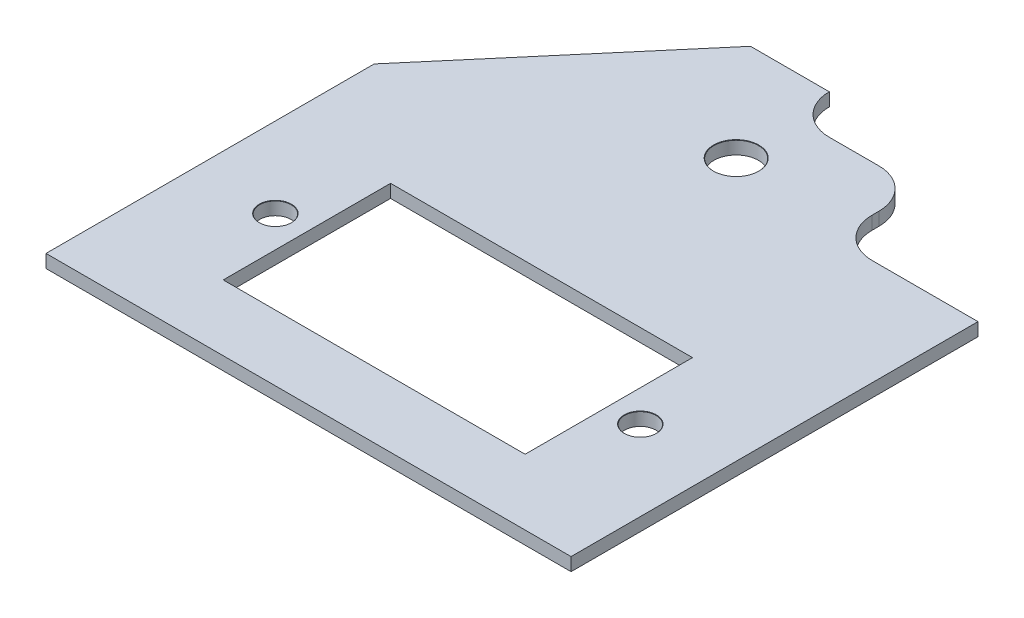
SolidWorks part; units mm, degrees
ref_plane "Front Plane" through (0, 0, 0) normal (0, 0, 1) x (1, 0, 0)
ref_plane "Top Plane" through (0, 0, 0) normal (0, 1, 0) x (1, 0, 0)
ref_plane "Right Plane" through (0, 0, 0) normal (1, 0, 0) x (0, 0, -1)
sketch "Sketch1" plane through (0, 0, 0) normal (0, 1, 0) x (1, 0, 0)
  line L0 (-3, 0) -> (-9, 0)
  line L5 (0, -3) -> (3.77, -3)
  line L6 (6.77, -6) -> (6.77, -6.5)
  line L7 (9.77, -6.5) -> (6.77, -6.5) construction
  line L8 (9.77, -9.5) -> (9.77, -15.5)
  line L9 (-9, 0) -> (-9, -15.5)
  line L10 (-9, -15.5) -> (9.77, -15.5)
  arc A0 (-3, 0) -> (0, -3) centre (0, 0) ccw
  arc A1 (6.77, -6) -> (3.77, -3) centre (3.77, -6) ccw
  arc A2 (6.77, -6.5) -> (9.77, -9.5) centre (9.77, -6.5) ccw
  dimension "D1" = 6
  dimension "D2" = 6
  dimension "D3" = 0.5
  dimension "D4" = 3.77
extrude "Boss-Extrude1" add sketch "Sketch1" along normal blind 1 contours L9 L10 L8 A2 L6 A1 L5 A0 L0
hole_wizard "M3 Clearance Hole1" positions "Sketch2" profile "Sketch3" hole size "M3" standard "ANSI Metric" end condition through all
sketch "Sketch2" plane through (0, 1, 0) normal (0, 1, 0) x (1, 0, 0)
  line L1 (-2.1713, -7.9213) -> (-2.1213, -7.9213) construction
  line L2 (-2.1213, -7.9213) -> (-2.1213, -2.1213) construction
  arc A1 (-3, 0) -> (0, -3) centre (0, 0) ccw construction
  point P0 (-2.1713, -7.9213)
  dimension "D1" = 5.8
  dimension "D2" = 0.05
sketch "Sketch3" plane through (-2.1713, 1, 7.9213) normal (1, 0, 0) x (0, 0, 1)
  line L0 (0, 0) -> (0, 1)
  line L1 (0, 1) -> (1.7, 1)
  line L2 (1.7, 1) -> (1.7, 0.025)
  line L3 (1.7, 0.025) -> (1.725, 0)
  line L5 (1.725, 0) -> (0, 0)
  line L6 (-1.7, 0.025) -> (-1.725, 0) construction
  line L11 (0, -6.35) -> (0, 107.95) construction
  dimension "Thru Hole Dia." = 3.4
  dimension "Thru Hole Depth" = 1
  dimension "Near C'Sink Dia." = 3.45
  dimension "Near C'Sink Angle" = 90
sketch "Sketch4" plane through (0, 1, 0) normal (0, 1, 0) x (1, 0, 0)
  line L0 (-9, -15.5) -> (9.77, -15.5) construction
  line L1 (-22.1713, -15.5) -> (17.8287, -15.5)
  line L2 (-22.1713, -15.5) -> (-22.1713, -40.5)
  line L3 (-22.1713, -40.5) -> (17.8287, -40.5)
  line L4 (17.8287, -40.5) -> (17.8287, -15.5)
  circle A0 centre (-2.1713, -7.9213) radius 1.725 construction
  circle A1 centre (-2.1713, -7.9213) radius 1.725 construction
  point P10 (-2.1713, -15.5)
  dimension "D1" = 40
  dimension "D2" = 25
extrude "Boss-Extrude2" add sketch "Sketch4" against normal up to surface (1 mm away) up to face at (-2.1713, 0, 9.6213)
sketch "Sketch5" plane through (0, 1, 0) normal (0, 1, 0) x (1, 0, 0)
  line L0 (17.8287, -15.5) -> (9.77, -15.5) construction
  line L1 (9.77, -9.5) -> (9.77, -15.5) construction
  line L2 (17.8287, -15.5) -> (9.77, -15.5)
  line L3 (9.77, -9.5) -> (9.77, -15.5)
  line L4 (9.77, -9.5) -> (17.8287, -9.5)
  line L5 (17.8287, -9.5) -> (17.8287, -15.5)
  line L6 (-9, -15.5) -> (-22.1713, -15.5) construction
  line L7 (-9, 0) -> (-9, -15.5) construction
  line L8 (-9, -15.5) -> (-22.1713, -15.5)
  line L9 (-9, 0) -> (-9, -15.5)
  line L12 (-22.1713, -15.5) -> (-9, 0)
extrude "Boss-Extrude3" add sketch "Sketch5" against normal up to surface (1 mm away) up to face at (-2.1713, 0, 9.6213)
sketch "Sketch8" plane through (0, 1, 0) normal (0, 1, 0) x (1, 0, 0)
  line L0 (-22.1713, -15.5) -> (17.8287, -15.5) construction
  line L1 (17.8287, -40.5) -> (17.8287, -9.5) construction
  line L2 (-2.1713, -29.125) -> (-2.1713, -7.9213) construction
  line L3 (-13.6713, -22.75) -> (9.3287, -22.75)
  line L4 (-13.6713, -22.75) -> (-13.6713, -35.5)
  line L5 (-13.6713, -35.5) -> (9.3287, -35.5)
  line L6 (9.3287, -22.75) -> (9.3287, -35.5)
  line L7 (-13.6713, -22.75) -> (9.3287, -35.5) construction
  line L8 (-13.6713, -35.5) -> (9.3287, -22.75) construction
  line L9 (-22.1713, -40.5) -> (17.8287, -40.5) construction
  circle A1 centre (-2.1713, -7.9213) radius 1.725 construction
  circle A2 centre (-2.1713, -7.9213) radius 1.725 construction
  point P5 (-2.1713, -29.125)
  dimension "D1" = 23
  dimension "D2" = 12.75
  dimension "D3" = 5
extrude "Cut-Extrude1" cut sketch "Sketch8" against normal up to surface (1 mm away) contours L4 L5 L6 L3 up to face at (-2.1713, 0, 9.6213)
hole_wizard "M2 Clearance Hole1" positions "Sketch9" profile "Sketch10" hole size "M2" standard "ANSI Metric" end condition through all
sketch "Sketch9" plane through (0, 1, 0) normal (0, 1, 0) x (1, 0, 0)
  line L0 (-16.0713, -29.125) -> (11.7287, -29.125) construction
  line L1 (-2.1713, -29.125) -> (-2.1713, -22.75) construction
  line L2 (-13.6713, -22.75) -> (9.3287, -22.75) construction
  line L3 (-2.1713, -29.125) -> (-2.1713, -35.5) construction
  line L4 (-13.6713, -35.5) -> (9.3287, -35.5) construction
  line L5 (-22.1713, -15.5) -> (17.8287, -15.5) construction
  line L6 (17.8287, -40.5) -> (17.8287, -9.5) construction
  point P0 (-16.0713, -29.125)
  point P2 (11.7287, -29.125)
  dimension "D1" = 27.8
sketch "Sketch10" plane through (-16.0713, 1, 29.125) normal (1, 0, 0) x (0, 0, 1)
  line L0 (0, 0) -> (0, 1)
  line L1 (0, 1) -> (1.2, 1)
  line L2 (1.2, 1) -> (1.2, 0.025)
  line L3 (1.2, 0.025) -> (1.225, 0)
  line L5 (1.225, 0) -> (0, 0)
  line L6 (-1.2, 0.025) -> (-1.225, 0) construction
  line L11 (0, -6.35) -> (0, 107.95) construction
  dimension "Thru Hole Dia." = 2.4
  dimension "Thru Hole Depth" = 1
  dimension "Near C'Sink Dia." = 2.45
  dimension "Near C'Sink Angle" = 90
